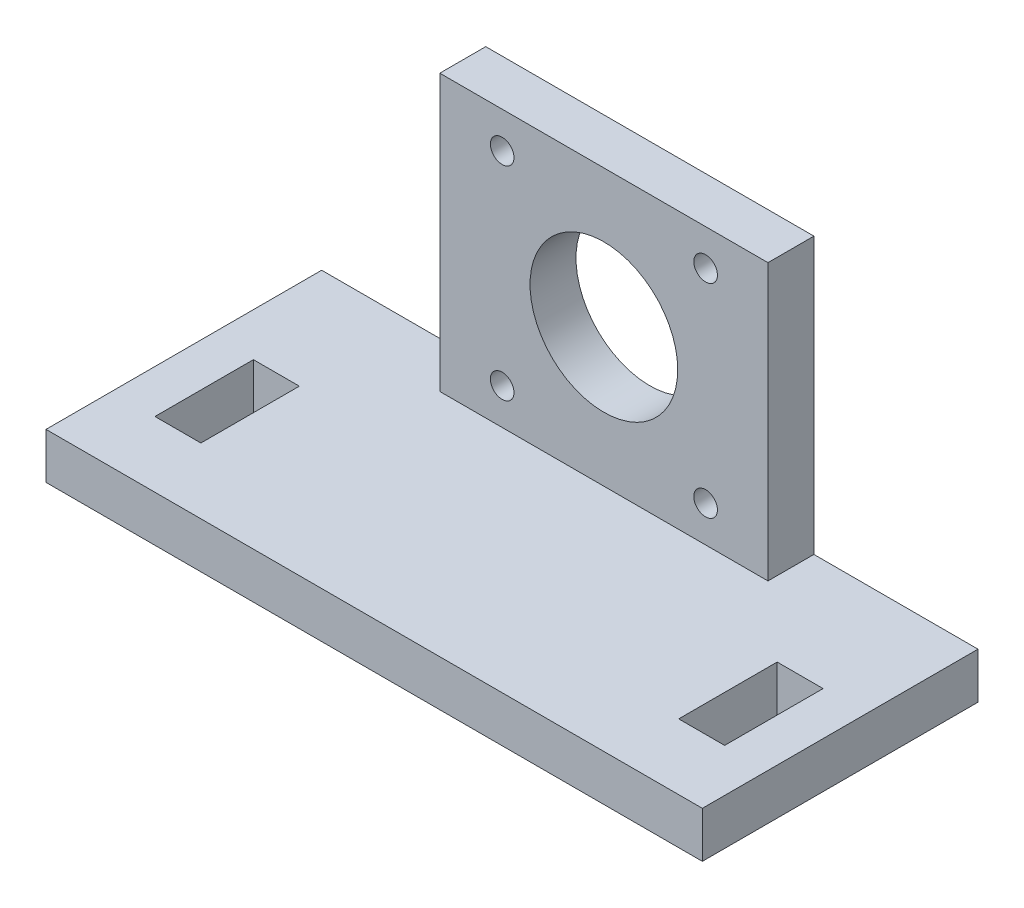
SolidWorks part; units mm, degrees
ref_plane "Front Plane" through (0, 0, 0) normal (0, 0, 1) x (1, 0, 0)
ref_plane "Top Plane" through (0, 0, 0) normal (0, 1, 0) x (1, 0, 0)
ref_plane "Right Plane" through (0, 0, 0) normal (1, 0, 0) x (0, 0, -1)
sketch "Sketch1" plane through (0, 0, 0) normal (0, 1, 0) x (1, 0, 0)
  line L1 (-25, -21) -> (25, -21)
  line L2 (-25, -21) -> (-25, 21)
  line L3 (-25, 21) -> (25, 21)
  line L4 (25, -21) -> (25, 21)
  line L5 (-25, -21) -> (25, 21) construction
  line L6 (-25, 21) -> (25, -21) construction
  point P0 (0, 0)
  dimension "D1" = 50
  dimension "D2" = 42
extrude "Boss-Extrude1" add sketch "Sketch1" along normal blind 49
sketch "Sketch2" plane through (0, 49, 0) normal (0, 1, 0) x (1, 0, 0)
  line L0 (25, -21) -> (25, 21) construction
  line L1 (-25, -21) -> (25, -21)
  line L2 (-25, -21) -> (-25, 14)
  line L3 (-25, 14) -> (25, 14)
  line L4 (25, -21) -> (25, 14)
  dimension "D1" = 35
extrude "Cut-Extrude1" cut sketch "Sketch2" against normal blind 42
sketch "Sketch3" plane through (25, 0, 0) normal (1, 0, 0) x (0, 0, -1)
  line L0 (21, 49) -> (21, 0) construction
  line L1 (-21, 0) -> (21, 0)
  line L2 (-21, 0) -> (-21, 7)
  line L3 (-21, 7) -> (21, 7)
  line L4 (21, 0) -> (21, 7)
  dimension "D1" = 7
extrude "Boss-Extrude2" add sketch "Sketch3" along normal blind 25
sketch "Sketch4" plane through (-25, 0, 0) normal (-1, 0, 0) x (0, 0, 1)
  line L1 (21, 7) -> (-21, 7)
  line L2 (21, 7) -> (21, 0)
  line L3 (21, 0) -> (-21, 0)
  line L4 (-21, 7) -> (-21, 0)
extrude "Boss-Extrude3" add sketch "Sketch4" along normal blind 25
sketch "Sketch5" plane through (0, 0, -14) normal (0, 0, 1) x (1, 0, 0)
  line L0 (25, 49) -> (-25, 49) construction
  line L1 (-25, 7) -> (-25, 49) construction
  circle A0 centre (0, 28) radius 11.25
  circle A1 centre (-15.5, 43.5) radius 1.8
  circle A2 centre (15.5, 43.5) radius 1.8
  circle A3 centre (-15.5, 12.5) radius 1.8
  circle A4 centre (15.5, 12.5) radius 1.8
  dimension "D1" = 22.5
  dimension "D3" = 3.6
  dimension "D2" = 21
  dimension "D4" = 5.5
  dimension "D5" = 9.5
  dimension "D6" = 2
  dimension "D7" = 2
  dimension "D8" = 2
extrude "Cut-Extrude2" cut sketch "Sketch5" against normal through all
sketch "Sketch6" plane through (0, 7, 0) normal (0, 1, 0) x (1, 0, 0)
  line L0 (-50, -21) -> (-50, 21) construction
  line L1 (-43.4, -11) -> (-36.4, -11)
  line L2 (-43.4, -11) -> (-43.4, 4)
  line L3 (-43.4, 4) -> (-36.4, 4)
  line L4 (-36.4, -11) -> (-36.4, 4)
  line L5 (36.4, -11) -> (43.4, -11)
  line L6 (36.4, -11) -> (36.4, 4)
  line L7 (36.4, 4) -> (43.4, 4)
  line L8 (43.4, -11) -> (43.4, 4)
  line L9 (50, 21) -> (50, -21) construction
  line L10 (-50, -21) -> (50, -21) construction
  dimension "D1" = 7
  dimension "D2" = 7
  dimension "D3" = 6.6
  dimension "D4" = 6.6
  dimension "D5" = 15
  dimension "D6" = 15
  dimension "D7" = 10
  dimension "D8" = 10
extrude "Cut-Extrude3" cut sketch "Sketch6" against normal through all
